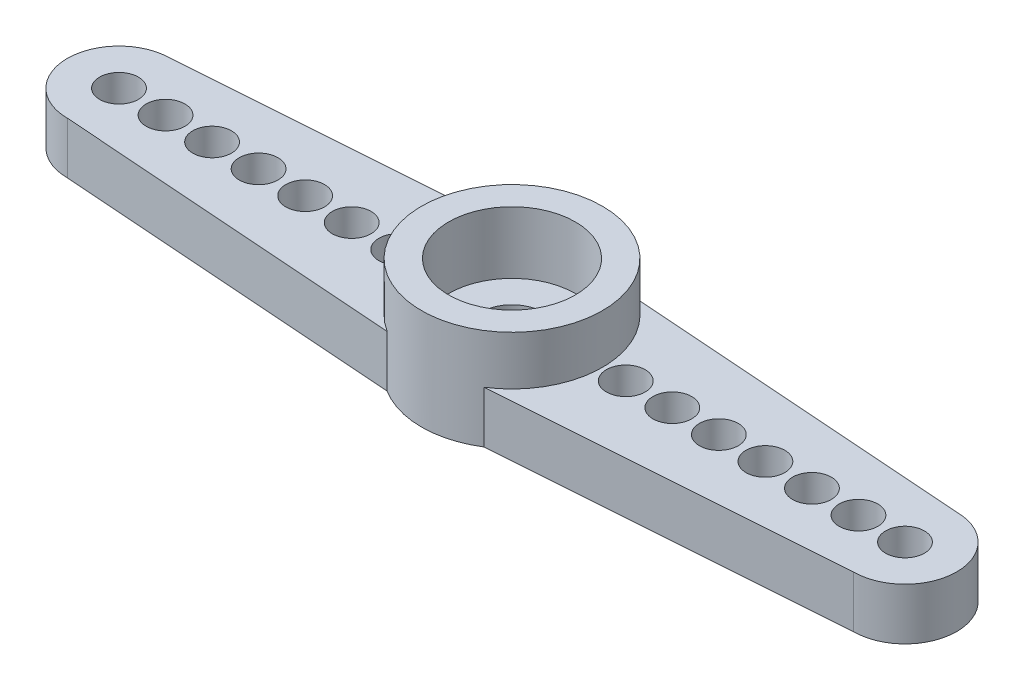
SolidWorks part; units mm, degrees
ref_plane "Front Plane" through (0, 0, 0) normal (0, 0, 1) x (1, 0, 0)
ref_plane "Top Plane" through (0, 0, 0) normal (0, 1, 0) x (1, 0, 0)
ref_plane "Right Plane" through (0, 0, 0) normal (1, 0, 0) x (0, 0, -1)
sketch "Sketch1" plane through (0, 0, 0) normal (0, 0, 1) x (1, 0, 0)
  line L0 (3.5, 3.9) -> (0, 3.9)
  line L1 (0, 3.9) -> (0, 0)
  line L2 (0, 0) -> (3.5, 0)
  line L3 (3.5, 0) -> (3.5, 3.9)
  line L4 (0, 3.9) -> (0, 0) construction
revolve "Revolve1" add sketch "Sketch1" angle 360 about L4
ref_plane "Plane1" through (0, 0, 0) normal (0, -1, 0) x (1, 0, 0)
sketch "Sketch2" plane through (0, 0, 0) normal (0, -1, 0) x (1, 0, 0)
  line L0 (-1.8686, 2.9595) -> (-15.2, 2)
  line L1 (-15.2, -2) -> (-1.8686, -2.9595)
  arc A0 (-15.2, 2) -> (-15.2, -2) centre (-15.2, 0) ccw
  arc A1 (-1.8686, -2.9595) -> (-1.8686, 2.9595) centre (0, 0) cw
extrude "Boss-Extrude1" add sketch "Sketch2" against normal blind 2
sketch "Sketch3" plane through (0, 0, 0) normal (0, -1, 0) x (1, 0, 0)
  line L0 (1.8686, -2.9595) -> (15.2, -2)
  line L1 (15.2, 2) -> (1.8686, 2.9595)
  arc A0 (1.8686, 2.9595) -> (1.8686, -2.9595) centre (0, 0) cw
  arc A1 (15.2, -2) -> (15.2, 2) centre (15.2, 0) ccw
extrude "Boss-Extrude2" add sketch "Sketch3" against normal blind 2
sketch "Sketch4" plane through (0, 0, 0) normal (0, 0, 1) x (1, 0, 0)
  line L0 (2.45, 3.9) -> (0, 3.9)
  line L1 (0, 3.9) -> (0, 0)
  line L2 (0, 0) -> (2.35, 0)
  line L3 (2.35, 0) -> (2.35, 1)
  line L4 (2.35, 1) -> (1.2, 1)
  line L5 (1.2, 1) -> (1.2, 1.5)
  line L6 (1.2, 1.5) -> (2.45, 1.5)
  line L7 (2.45, 1.5) -> (2.45, 3.9)
  line L8 (0, 3.9) -> (0, 0) construction
revolve "Cut-Revolve1" cut sketch "Sketch4" angle 360 about L8
hole_wizard "Ø1.5mm Dowel Hole1" positions "Sketch6" profile "Sketch5" hole size "Ø1.5" standard "ANSI Metric" end condition through all
sketch "Sketch6" plane through (0, 0, 0) normal (0, -1, 0) x (-1, 0, 0)
  point P0 (15.2, 0)
  point P1 (-15.2, 0)
  point P2 (13.4, 0)
  point P3 (11.6, 0)
  point P4 (9.8, 0)
  point P5 (8, 0)
  point P6 (6.2, 0)
  point P7 (4.4, 0)
  point P8 (-13.4, 0)
  point P9 (-11.6, 0)
  point P10 (-9.8, 0)
  point P11 (-8, 0)
  point P12 (-6.2, 0)
  point P13 (-4.4, 0)
sketch "Sketch5" plane through (-15.2, 0, 0) normal (1, 0, 0) x (0, 0, -1)
  line L0 (0, 0) -> (0, 3.9)
  line L1 (0, 3.9) -> (0.75, 3.9)
  line L2 (0.75, 3.9) -> (0.75, 0)
  line L5 (0.75, 0) -> (0, 0)
  line L11 (0, -6.35) -> (0, 107.95) construction
  dimension "Thru Hole Dia." = 1.5
  dimension "Thru Hole Depth" = 3.9
